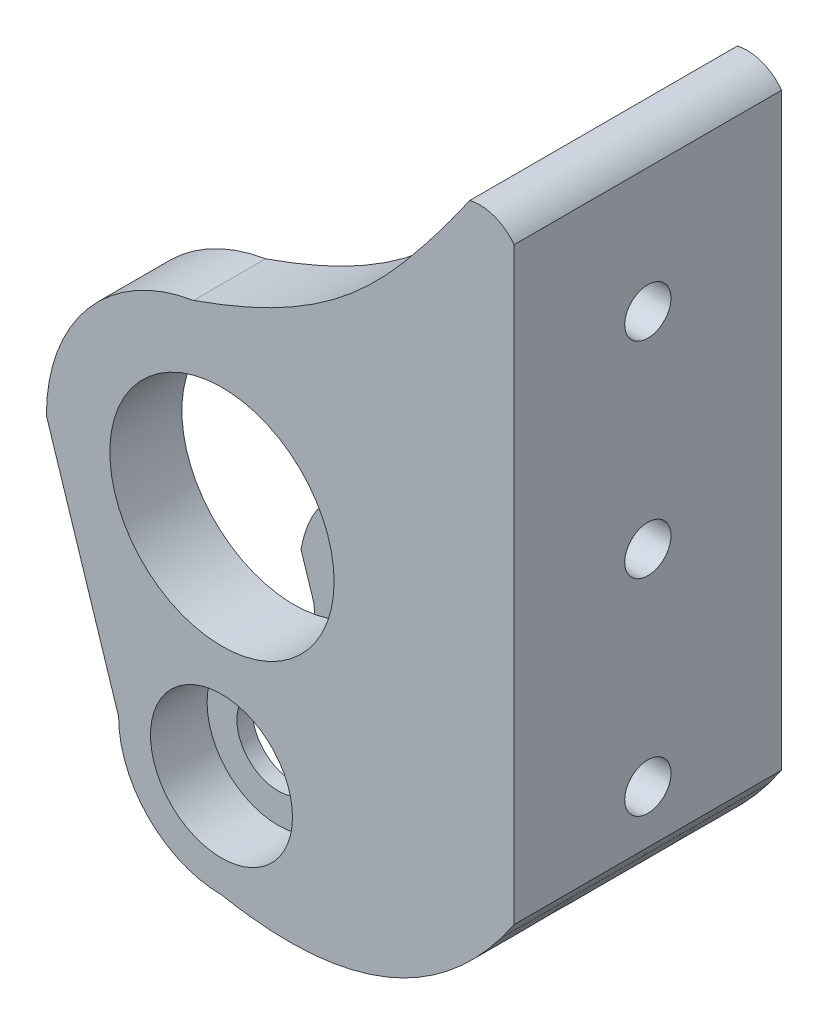
SolidWorks part; units mm, degrees
ref_plane "Front Plane" through (0, 0, 0) normal (0, 0, 1) x (1, 0, 0)
ref_plane "Top Plane" through (0, 0, 0) normal (0, 1, 0) x (1, 0, 0)
ref_plane "Right Plane" through (0, 0, 0) normal (1, 0, 0) x (0, 0, -1)
sketch "Sketch1" plane through (0, 0, 0) normal (0, 0, 1) x (1, 0, 0)
  line L0 (-124.2968, 47.657) -> (-117.2775, 25.8121)
  line L1 (-80.0553, 84.3442) -> (-80.0553, 25.8121)
  circle A0 centre (-107.23, 47.657) radius 10.9
  circle A1 centre (-107.2775, 25.8121) radius 6.9
  arc A2 (-109.9929, 64.4987) -> (-124.2968, 47.657) centre (-107.23, 47.657) ccw
  arc A3 (-117.2774, 25.8556) -> (-107.2775, 15.8121) centre (-107.2775, 25.8121) ccw
  arc A4 (-83.6647, 85.5315) -> (-80.0553, 84.3442) centre (-82.0553, 84.3442) cw
  spline S0 degree 3 poles (-109.9929, 64.4987) (-95.7368, 69.4712) (-91.1309, 75.4105) (-83.6647, 85.5315) knots 0 0 0 0 0.858728 0.858728 0.858728 0.858728
  spline S1 degree 2 poles (-80.0553, 25.8121) (-90.1657, 12.4948) (-107.2775, 15.8121) knots 0 0 0 1 1 1
extrude "Boss-Extrude1" add sketch "Sketch1" along normal blind 7 contours S1 L1 A4 S0 A2 L0 A3 A1 A0
sketch "Sketch2" plane through (0, 0, 7) normal (0, 0, 1) x (1, 0, 0)
  line L0 (-85.0553, 83.6537) -> (-85.0553, 20.5833)
  line L2 (-80.0553, 25.8121) -> (-80.0553, 84.3442)
  line L3 (-121.1024, 37.7156) -> (-115.4058, 19.987)
  line L4 (-80.0553, 25.8121) -> (-80.0553, 84.3442)
  arc A3 (-80.0553, 84.3442) -> (-83.6647, 85.5315) centre (-82.0553, 84.3442) ccw
  arc A4 (-109.9929, 64.4987) -> (-121.1024, 37.7156) centre (-107.23, 47.657) ccw
  arc A5 (-115.4058, 19.987) -> (-107.2775, 15.8121) centre (-107.2775, 25.8121) ccw
  arc A6 (-80.0553, 84.3442) -> (-83.6647, 85.5315) centre (-82.0553, 84.3442) ccw
  parabola Q1 (-107.2775, 15.8121) -> (-80.0553, 25.8121) focus (-95.4224, 27.7636) apex (-90.9126, 17.0487)
  parabola Q2 (-85.0553, 20.5833) -> (-80.0553, 25.8121) focus (-95.4224, 27.7636) apex (-90.9126, 17.0487)
  spline S1 degree 3 poles (1729.154, 923.3668) (-1823.5702, -431.2559) (1701.6954, 411.3928) (-2085.4377, -246.693) knots -4.229152 -4.229152 -4.229152 -4.229152 4.76838 4.76838 4.76838 4.76838 only from (-83.6647, 85.5315) to (-109.9929, 64.4987)
  spline S2 degree 3 poles (-83.6647, 85.5315) (-84.1387, 84.889) (-84.6011, 84.2633) (-85.0553, 83.6537) knots 0 0 0 0 0.054514 0.054514 0.054514 0.054514
  dimension "D2" = 5
  dimension "D1" = 0
extrude "Boss-Extrude2" add sketch "Sketch2" along normal blind 12
ref_plane "Plane1" through (0, 0, 13) normal (0, 0, 1) x (1, 0, 0)
mirror "Mirror1" about plane through (0, 0, 13) normal (0, 0, 1) of "Boss-Extrude1"
sketch "Sketch3" plane through (0, 0, 0) normal (0, 0, -1) x (-1, 0, 0)
  line L0 (124.2968, 47.657) -> (117.2775, 25.8121) construction
  line L1 (92.8505, 74.3977) -> (144.5312, 88.8658)
  line L2 (144.5312, 88.8658) -> (118.5461, 29.7602)
  circle A0 centre (107.23, 47.657) radius 10.9 construction
  arc A1 (96.33, 47.657) -> (107.23, 36.757) centre (107.23, 47.657) ccw
  spline S0 degree 2 poles (92.8505, 74.3977) (90.4236, 60.1608) (96.33, 47.657) knots 0 0 0 1 1 1
  spline S1 degree 3 poles (109.9929, 64.4987) (95.7368, 69.4712) (91.1309, 75.4105) (83.6647, 85.5315) knots 0 0 0 0 0.858728 0.858728 0.858728 0.858728 construction
  spline S2 degree 2 poles (107.23, 36.757) (116.8643, 38.6004) (118.5461, 29.7602) knots 0 0 0 1 1 1
extrude "Cut-Extrude1" cut sketch "Sketch3" against normal blind 13
sketch "Sketch4" plane through (0, 0, 0) normal (0, 0, -1) x (-1, 0, 0)
  line L1 (78.83, 3.461) -> (78.83, 91.853) construction
  line L2 (83.1328, 86.3442) -> (85.0553, 83.6537)
  line L4 (78.83, 84.7703) -> (78.83, 27.533)
  line L6 (85.0553, 83.6537) -> (85.0553, 20.5833) construction
  line L7 (85.0553, 83.6537) -> (85.0553, 20.5878)
  arc A7 (83.1328, 86.3442) -> (78.83, 84.7703) centre (82.1807, 82.2784) ccw
  parabola Q7 (78.83, 27.533) -> (85.0553, 20.5878) focus (95.4245, 27.7656) apex (90.9128, 17.0515)
extrude "Boss-Extrude3" add sketch "Sketch4" against normal up to vertex (26 mm away) up to point (-80.0553, 25.8121, 26)
sketch "Sketch5" plane through (0, 0, 7) normal (0, 0, 1) x (1, 0, 0)
  circle A0 centre (-107.2775, 25.8121) radius 7.9739
  circle A1 centre (-107.2775, 25.8121) radius 4
  dimension "D1" = 8
extrude "Boss-Extrude4" add sketch "Sketch5" against normal blind 1.5
sketch "Sketch6" plane through (0, 0, 19) normal (0, 0, -1) x (-1, 0, 0)
  circle A0 centre (107.2775, 25.8121) radius 8.4911
  circle A1 centre (107.2775, 25.8121) radius 4
  dimension "D1" = 8
extrude "Boss-Extrude5" add sketch "Sketch6" against normal blind 1.5
sketch "Sketch7" plane through (-85.0553, 0, 0) normal (-1, 0, 0) x (0, 0, 1)
  line L0 (13, -18.42) -> (13, 18.42) construction
  line L1 (19, 83.6537) -> (7, 83.6537) construction
  circle A0 centre (13, 32.6537) radius 2.25
  circle A1 centre (13, 52.6537) radius 2.25
  circle A2 centre (13, 72.6537) radius 2.25
  dimension "D1" = 4.5
  dimension "D2" = 4.5
  dimension "D3" = 4.5
  dimension "D4" = 20
  dimension "D5" = 20
  dimension "D6" = 11
extrude "Cut-Extrude2" cut sketch "Sketch7" against normal through all
